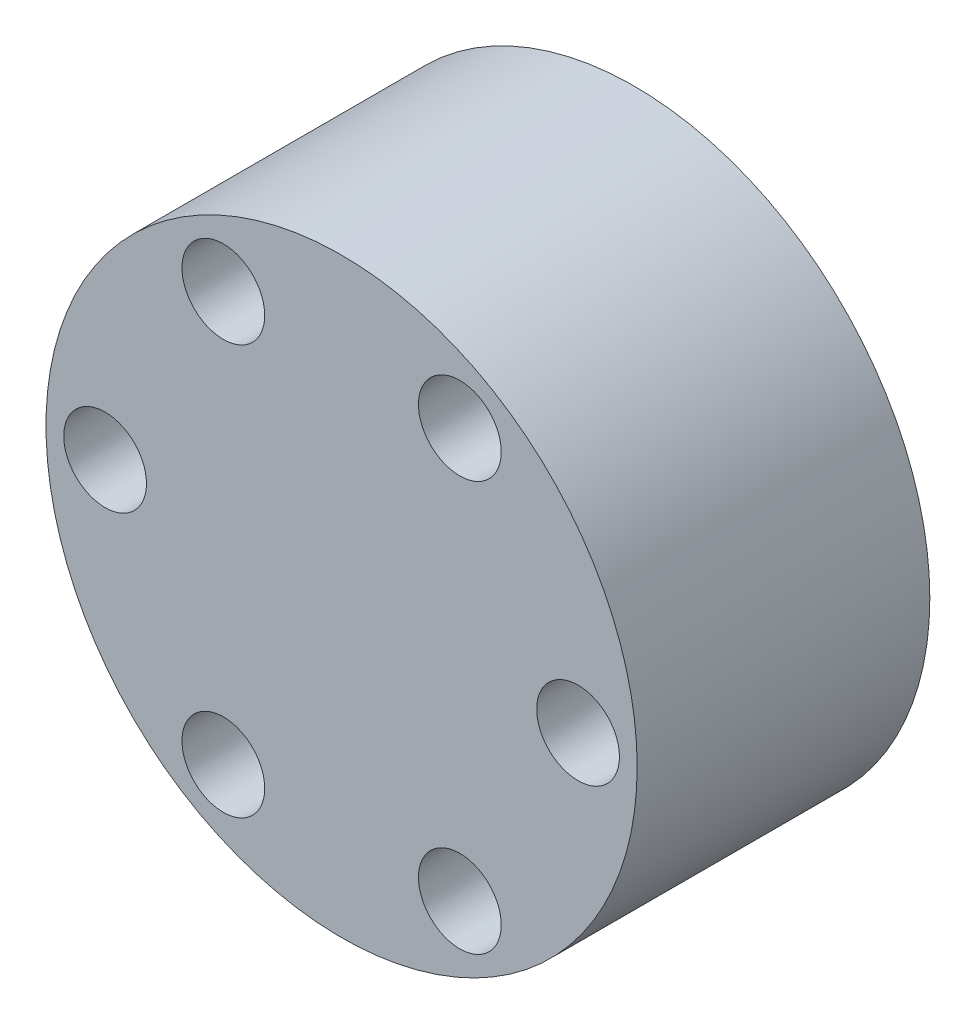
SolidWorks part; units mm, degrees
ref_plane "Front Plane" through (0, 0, 0) normal (0, 0, 1) x (1, 0, 0)
ref_plane "Top Plane" through (0, 0, 0) normal (0, 1, 0) x (1, 0, 0)
ref_plane "Right Plane" through (0, 0, 0) normal (1, 0, 0) x (0, 0, -1)
sketch "Sketch1" plane through (0, 0, 0) normal (0, 0, 1) x (1, 0, 0)
  circle A0 centre (0, 0) radius 15
  dimension "D1" = 30
extrude "Boss-Extrude1" add sketch "Sketch1" along normal mid plane 14.85
sketch "Sketch2" plane through (0, 0, 7.425) normal (0, 0, 1) x (1, 0, 0)
  line L0 (0, 0) -> (-12, 0) construction
  circle A0 centre (-12, 0) radius 2.1
  circle A1 centre (-6, 10.3923) radius 2.1
  circle A2 centre (6, 10.3923) radius 2.1
  circle A3 centre (12, 0) radius 2.1
  circle A4 centre (6, -10.3923) radius 2.1
  circle A5 centre (-6, -10.3923) radius 2.1
  point P5 (-9.3595, -13.5082)
  point P6 (0, 0)
  point P16 (0, 0)
  dimension "D2" = 4.2
  dimension "D1" = 12
  dimension "D3" = 6
extrude "Cut-Extrude1" cut sketch "Sketch2" against normal through all contours A1 | A2 | A3 | A4 | A5 | A0
